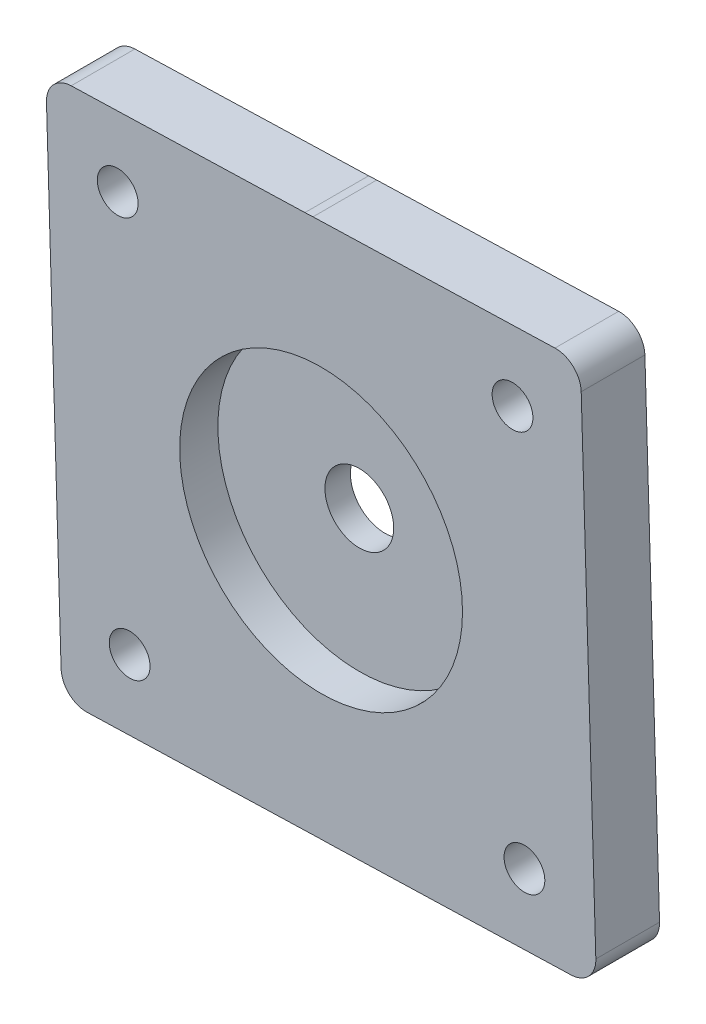
SolidWorks part; units mm, degrees
ref_plane "Front Plane" through (0, 0, 0) normal (0, 0, 1) x (1, 0, 0)
ref_plane "Top Plane" through (0, 0, 0) normal (0, 1, 0) x (1, 0, 0)
ref_plane "Right Plane" through (0, 0, 0) normal (1, 0, 0) x (0, 0, -1)
sketch "Sketch1" plane through (0, 0, 0) normal (0, 0, 1) x (1, 0, 0)
  line L14 (-1.2681, 20.9617) -> (-19.6158, 20.4072)
  line L15 (-21.5545, 18.3477) -> (-21, 0)
  line L16 (-20.9617, -1.2681) -> (-20.4072, -19.6158)
  line L17 (-18.3477, -21.5545) -> (0, -21)
  line L18 (0.6343, -20.9904) -> (19.6257, -20.4165)
  line L19 (21.5643, -18.357) -> (20.4165, 19.6257)
  line L20 (18.357, 21.5643) -> (-0.6343, 20.9904)
  circle A4 centre (15.9611, -15.0247) radius 1.6
  circle A5 centre (-15.0247, -15.9611) radius 1.6
  circle A6 centre (-15.9611, 15.0247) radius 1.6
  arc A14 (-19.6158, 20.4072) -> (-21.5545, 18.3477) centre (-19.5554, 18.4081) ccw
  arc A15 (-21, 0) -> (-20.9617, -1.2681) centre (0, 0) ccw
  arc A16 (-20.4072, -19.6158) -> (-18.3477, -21.5545) centre (-18.4081, -19.5554) ccw
  arc A17 (0, -21) -> (0.6343, -20.9904) centre (0, 0) ccw
  arc A18 (19.6257, -20.4165) -> (21.5643, -18.357) centre (19.5652, -18.4174) ccw
  arc A19 (20.4165, 19.6257) -> (18.357, 21.5643) centre (18.4174, 19.5652) ccw
  arc A20 (-0.6343, 20.9904) -> (-1.2681, 20.9617) centre (0, 0) ccw
  circle A21 centre (15.0247, 15.9611) radius 1.6
  circle A22 centre (0, 0) radius 30.3196
extrude "Boss-Extrude1" add sketch "Sketch1" along normal blind 5 contours L20 A20 L14 A14 L15 A15 L16 A16 L17 A17 L18 A18 L19 A19 A21 A4 A5 A6
sketch "Sketch3" plane through (0, 0, 5) normal (0, 0, 1) x (1, 0, 0)
  circle A0 centre (0, 0) radius 11.1
extrude "Cut-Extrude1" cut sketch "Sketch3" against normal blind 3
sketch "Sketch4" plane through (0, 0, 2) normal (0, 0, 1) x (1, 0, 0)
  circle A0 centre (0, 0) radius 2.7
extrude "Cut-Extrude2" cut sketch "Sketch4" against normal blind 3
